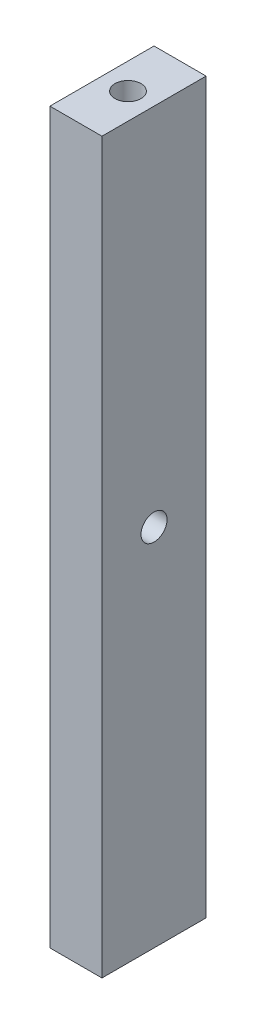
SolidWorks part; units mm, degrees
material "Custom Plastic"
ref_plane "X-Y Datum" through (0, 0, 0) normal (0, 0, 1) x (1, 0, 0)
ref_plane "X-Z Datum" through (0, 0, 0) normal (0, 1, 0) x (1, 0, 0)
ref_plane "Y-Z Datum" through (0, 0, 0) normal (1, 0, 0) x (0, 0, -1)
sketch "Sketch1" plane through (0, 0, 0) normal (0, 1, 0) x (1, 0, 0)
  line L1 (0, 0) -> (50.8, 0)
  line L2 (0, 0) -> (0, -101.6)
  line L3 (0, -101.6) -> (50.8, -101.6)
  line L4 (50.8, 0) -> (50.8, -101.6)
  dimension "D1" = 50.8
  dimension "D2" = 101.6
extrude "Boss-Extrude1" add sketch "Sketch1" against normal blind 711.2
sketch "Sketch2" plane through (0, 0, 0) normal (-1, 0, 0) x (0, 0, 1)
  line L0 (0, 0) -> (101.6, 0) construction
  line L1 (101.6, -711.2) -> (101.6, 0) construction
  circle A0 centre (50.8, -355.6) radius 12.7
  point P4 (50.8, 0)
  point P7 (101.6, -355.6)
  dimension "D1" = 25.4
extrude "Cut-Extrude1" cut sketch "Sketch2" against normal up to surface (50.8 mm away) up to face at (50.8, -355.6, 50.8)
sketch "Sketch3" plane through (0, 0, 0) normal (0, 1, 0) x (1, 0, 0)
  line L0 (50.8, -101.6) -> (50.8, 0) construction
  line L1 (0, -101.6) -> (50.8, -101.6) construction
  circle A0 centre (25.4, -50.8) radius 12.7
  point P5 (50.8, -50.8)
  point P9 (25.4, -101.6)
  dimension "D1" = 25.4
extrude "Cut-Extrude2" cut sketch "Sketch3" against normal blind 152.4
sketch "Sketch4" plane through (0, -711.2, 0) normal (0, -1, 0) x (1, 0, 0)
  circle A0 centre (25.4, 50.8) radius 12.7
  circle A1 centre (25.4, 50.8) radius 12.7 construction
extrude "Cut-Extrude3" cut sketch "Sketch4" against normal blind 152.4
ref_plane "Plane1" through (25.4, 0, 0) normal (1, 0, 0) x (0, 0, -1)
